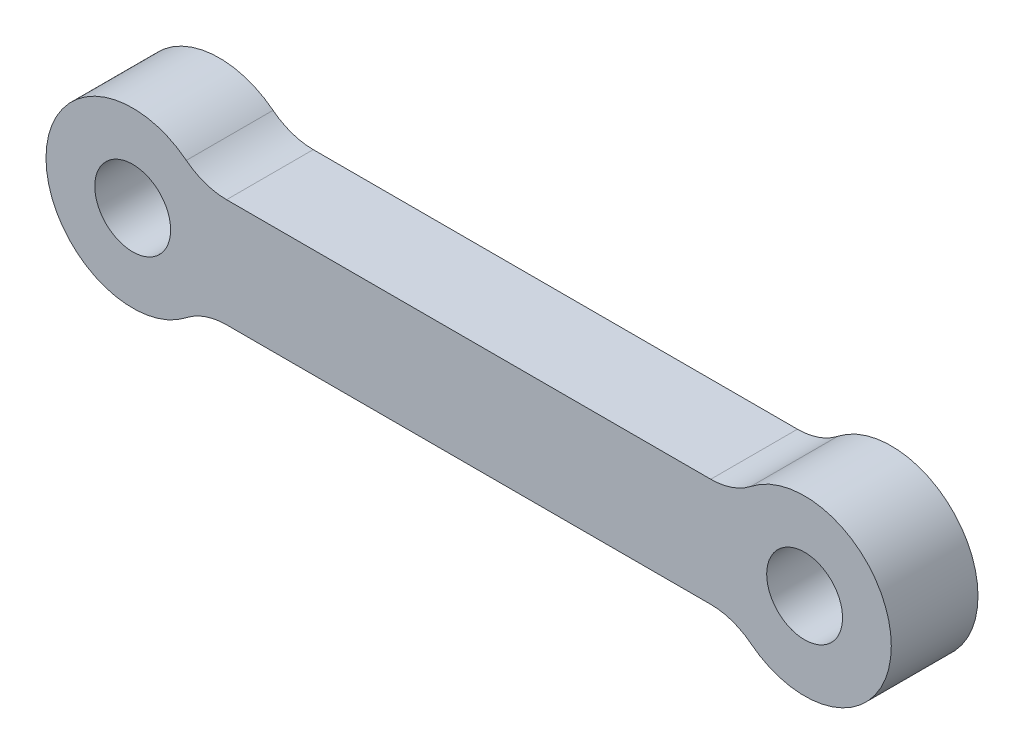
SolidWorks part; units mm, degrees
ref_plane "Front Plane" through (0, 0, 0) normal (0, 0, 1) x (1, 0, 0)
ref_plane "Top Plane" through (0, 0, 0) normal (0, 1, 0) x (1, 0, 0)
ref_plane "Right Plane" through (0, 0, 0) normal (1, 0, 0) x (0, 0, -1)
sketch "Sketch1" plane through (0, 0, 0) normal (0, 0, 1) x (1, 0, 0)
  line L61 (15.5, 2.5) -> (15.5, -2.5) construction
  line L62 (3.1225, 2.5) -> (27.8775, 2.5)
  line L63 (27.8775, -2.5) -> (3.1225, -2.5)
  circle A1 centre (0, 0) radius 1.75
  arc A8 (3.1225, 2.5) -> (3.1225, -2.5) centre (0, 0) ccw
  arc A9 (27.8775, 2.5) -> (27.8775, -2.5) centre (31, 0) cw
  circle A10 centre (31, 0) radius 1.75
  point P2 (15.5, 0)
  dimension "D1" = 8
  dimension "D4" = 3.5
  dimension "D5" = 15.5
  dimension "D6" = 5
extrude "Boss-Extrude1" add sketch "Sketch1" along normal blind 4
fillet "Fillet1" radius 3 4 edges at (27.8775, 2.5, 2) (27.8775, -2.5, 2) (3.1225, -2.5, 2) (3.1225, 2.5, 2)
ref_point "Point1"
ref_point "Point2"
